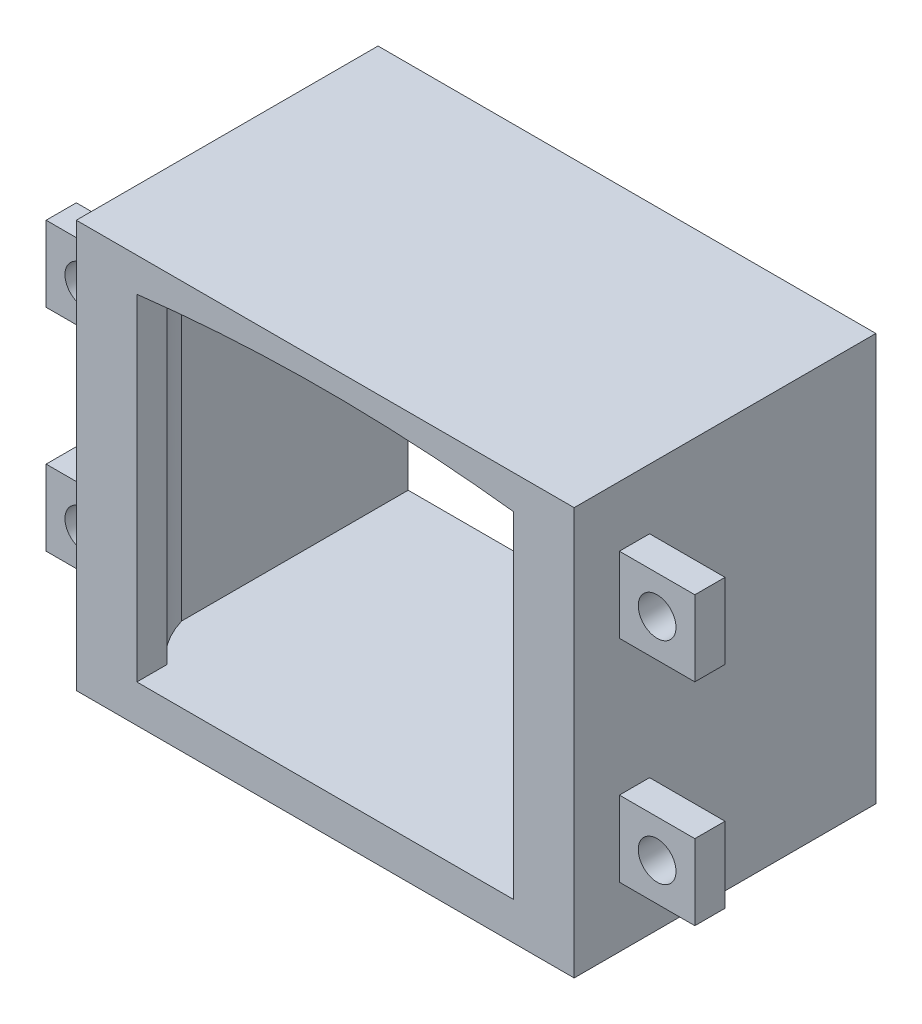
SolidWorks part; units mm, degrees
ref_plane "Front Plane" through (0, 0, 0) normal (0, 0, 1) x (1, 0, 0)
ref_plane "Top Plane" through (0, 0, 0) normal (0, 1, 0) x (1, 0, 0)
ref_plane "Right Plane" through (0, 0, 0) normal (1, 0, 0) x (0, 0, -1)
sketch "Sketch2" plane through (0, 0, 0) normal (0, 0, 1) x (1, 0, 0)
  line L1 (-16.5, -13.5) -> (16.5, -13.5)
  line L2 (-16.5, -13.5) -> (-16.5, 13.5)
  line L3 (-16.5, 13.5) -> (16.5, 13.5)
  line L4 (16.5, -13.5) -> (16.5, 13.5)
  line L5 (-16.5, -13.5) -> (16.5, 13.5) construction
  line L6 (-16.5, 13.5) -> (16.5, -13.5) construction
  point P0 (0, 0)
  dimension "D1" = 27
  dimension "D2" = 33
extrude "Boss-Extrude1" add sketch "Sketch2" against normal blind 20
sketch "Sketch3" plane through (0, 0, -20) normal (0, 0, -1) x (-1, 0, 0)
  line L0 (0, 11) -> (0, 12)
  line L2 (-14.5, 11) -> (-14.5, -11)
  line L3 (-14.5, -11) -> (14.5, -11)
  line L4 (14.5, 11) -> (14.5, -11)
  line L5 (-14.5, 11) -> (14.5, -11) construction
  line L6 (-14.5, -11) -> (14.5, 11) construction
  spline S0 degree 2 poles (-14.5, 11) (0, 13) (14.5, 11) knots 0 0 0 1 1 1
  point P0 (0, 0)
  dimension "D1" = 22
  dimension "D2" = 29
  dimension "D3" = 1
extrude "Cut-Extrude1" cut sketch "Sketch3" against normal blind 18
sketch "Sketch4" plane through (0, 13.5, 0) normal (0, 1, 0) x (1, 0, 0)
  line L0 (0, 0) -> (0, 20) construction
  line L1 (-16.5, 20) -> (-16.5, 0) construction
  line L2 (16.5, 0) -> (-16.5, 0) construction
  line L3 (-10.5531, 2) -> (-10.5531, 0)
  line L4 (-16.5, 5) -> (-14.5041, 5) construction
  line L5 (16.5, 20) -> (-16.5, 20) construction
  line L6 (-14.5041, 5) -> (-14.5041, 2)
  line L7 (-10.5531, 2) -> (-14.5041, 2) construction
  line L8 (-10.5531, 1) -> (-14.5041, 1)
  line L9 (-10.5531, 0) -> (10.5531, 0)
  line L10 (-10.5531, 0) -> (-10.5531, 2)
  line L11 (-10.5531, 2) -> (10.5531, 2)
  line L12 (0, 0) -> (0, 2)
  line L13 (-14.5041, 1) -> (-14.5041, 2)
  line L14 (10.5531, 0) -> (10.5531, 2)
  line L15 (10.5531, 2) -> (10.5531, 0)
  line L16 (10.5531, 2) -> (14.5041, 2) construction
  line L17 (14.5041, 1) -> (14.5041, 2)
  line L18 (10.5531, 1) -> (14.5041, 1)
  line L19 (14.5041, 5) -> (14.5041, 2)
  spline S0 degree 2 poles (-14.5041, 5) (-13.6269, 2.0369) (-10.5531, 1) knots 0 0 0 1 1 1
  spline S1 degree 2 poles (14.5041, 5) (13.6269, 2.0369) (10.5531, 1) knots 0 0 0 1 1 1
  point P13 (-13.5, 3)
  dimension "D1" = 2
  dimension "D2" = 1
  dimension "D3" = 3
  dimension "D4" = 5
extrude "Boss-Extrude3" add sketch "Sketch4" against normal blind 25 contours L19 S1 L18 L17 | S0 L6 L13 L8
sketch "Sketch9" plane through (0, 0, -2) normal (0, 0, -1) x (-1, 0, 0)
  line L0 (-12.4866, 11.2584) -> (-12.4866, -11)
  line L1 (-12.4866, -11) -> (12.4866, -11)
  line L2 (12.4866, -11) -> (12.4866, 11.2584)
  parabola Q0 (-12.4866, 11.2584) -> (12.4866, 11.2584) focus (0, -40.5625) apex (0, 12) construction
  spline S0 degree 2 poles (-12.4866, 11.2584) (0, 12.7416) (12.4866, 11.2584) knots 0 0 0 1 1 1
extrude "Cut-Extrude4" cut sketch "Sketch9" against normal blind 2
sketch "Sketch10" plane through (-16.5, 0, 0) normal (-1, 0, 0) x (0, 0, 1)
  line L0 (-20, -13.5) -> (0, -13.5) construction
  line L1 (-3, -13.5) -> (-5, -13.5)
  line L2 (-3, -13.5) -> (-3, 13.5)
  line L3 (-3, 13.5) -> (-5, 13.5)
  line L4 (-5, -13.5) -> (-5, 13.5)
  line L5 (-20, 13.5) -> (0, 13.5) construction
  line L6 (0, 13.5) -> (0, -13.5) construction
  line L7 (-3, 0) -> (-5, 0) construction
  line L8 (-5, 9.5) -> (-3, 9.5)
  line L9 (-5, 9.5) -> (-5, 4.5)
  line L10 (-5, 4.5) -> (-3, 4.5)
  line L11 (-3, 9.5) -> (-3, 4.5)
  line L12 (-5, -4.5) -> (-3, -4.5)
  line L13 (-3, -9.5) -> (-3, -4.5)
  line L14 (-5, -9.5) -> (-3, -9.5)
  line L15 (-5, -9.5) -> (-5, -4.5)
  dimension "D1" = 3
  dimension "D2" = 2
  dimension "D3" = 5
  dimension "D4" = 4
extrude "Boss-Extrude4" add sketch "Sketch10" along normal blind 5 contours L4 L10 L2 L8 | L4 L14 L2 L12
sketch "Sketch11" plane through (16.5, 0, 0) normal (1, 0, 0) x (0, 0, -1)
  line L0 (20, 13.5) -> (0, 13.5) construction
  line L1 (3, 13.5) -> (5, 13.5)
  line L2 (3, 13.5) -> (3, -13.5)
  line L3 (3, -13.5) -> (5, -13.5)
  line L4 (5, 13.5) -> (5, -13.5)
  line L5 (20, -13.5) -> (0, -13.5) construction
  line L6 (0, -13.5) -> (0, 13.5) construction
  line L7 (5, 0) -> (3, 0) construction
  line L8 (3, 9.5) -> (5, 9.5)
  line L9 (3, 9.5) -> (3, 4.5)
  line L10 (3, 4.5) -> (5, 4.5)
  line L11 (5, 9.5) -> (5, 4.5)
  line L12 (3, -4.5) -> (5, -4.5)
  line L13 (5, -9.5) -> (5, -4.5)
  line L14 (3, -9.5) -> (5, -9.5)
  line L15 (3, -9.5) -> (3, -4.5)
  dimension "D1" = 3
  dimension "D2" = 2
  dimension "D3" = 4
  dimension "D4" = 5
extrude "Boss-Extrude5" add sketch "Sketch11" along normal blind 5 contours L2 L10 L4 L8 | L2 L14 L4 L12
sketch "Sketch12" plane through (0, 0, -3) normal (0, 0, 1) x (1, 0, 0)
  line L0 (-21.5, 9.5) -> (-16.5, 4.5) construction
  line L1 (-21.5, 4.5) -> (-16.5, 4.5) construction
  line L2 (-21.5, 4.5) -> (-16.5, 9.5) construction
  line L3 (-21.5, 0) -> (-16.5, 0)
  line L4 (-21.5, 4.5) -> (-16.5, 4.5)
  line L5 (-21.5, 4.5) -> (-21.5, -4.5)
  line L6 (-21.5, -4.5) -> (-16.5, -4.5)
  line L7 (-16.5, 4.5) -> (-16.5, -4.5)
  line L8 (16.5, 0) -> (-16.5, 0)
  line L9 (16.5, 4.5) -> (21.5, 4.5)
  line L10 (16.5, 4.5) -> (16.5, -4.5)
  line L11 (16.5, -4.5) -> (21.5, -4.5)
  line L12 (21.5, 4.5) -> (21.5, -4.5)
  line L13 (0, 0) -> (0, -9.9947)
  circle A0 centre (-19, 7) radius 1.25
  circle A1 centre (-19, -7) radius 1.25
  circle A2 centre (19, -7) radius 1.25
  circle A3 centre (19, 7) radius 1.25
  dimension "D1" = 2.5
extrude "Cut-Extrude5" cut sketch "Sketch12" against normal blind 2 contours A2 | A3 | A0 | A1
